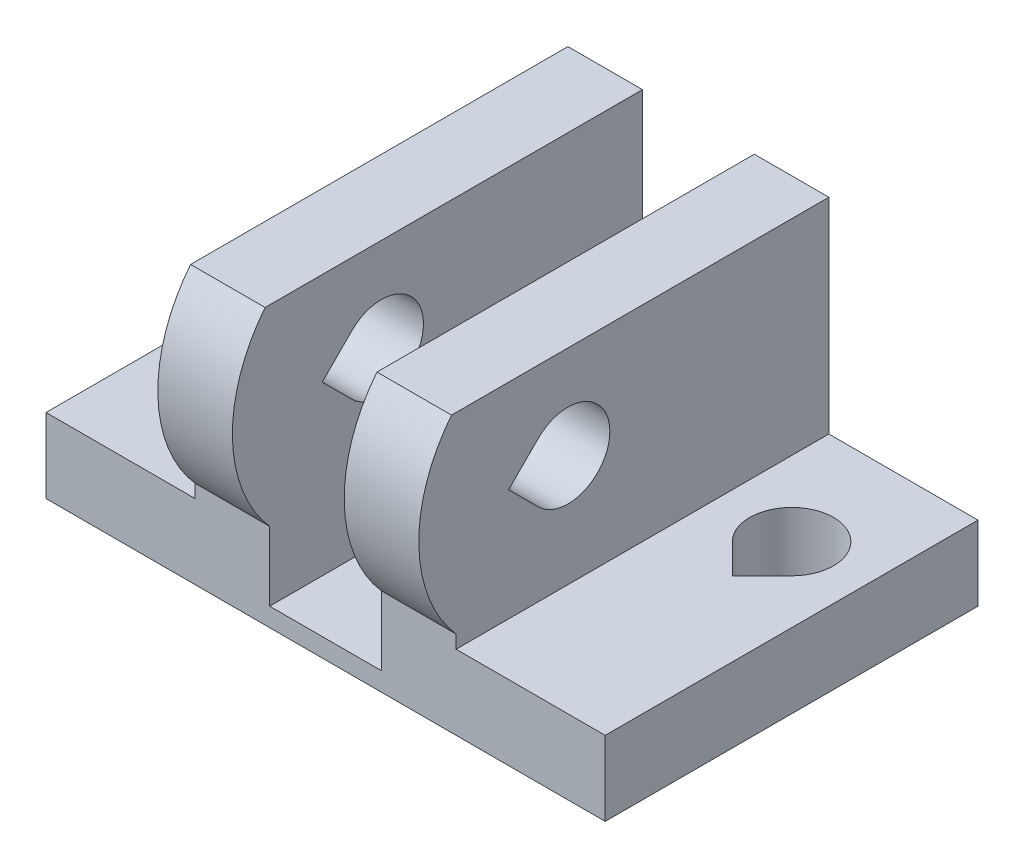
SolidWorks part; units mm, degrees
material "Printed PLA"
ref_plane "Front Plane" through (0, 0, 0) normal (0, 0, 1) x (1, 0, 0)
ref_plane "Top Plane" through (0, 0, 0) normal (0, 1, 0) x (1, 0, 0)
ref_plane "Right Plane" through (0, 0, 0) normal (1, 0, 0) x (0, 0, -1)
sketch "Sketch1" plane through (0, 0, 0) normal (0, 0, 1) x (1, 0, 0)
  line L0 (-15, 0) -> (15, 0)
  line L1 (15, 0) -> (15, 4)
  line L2 (15, 4) -> (7, 4)
  line L3 (7, 4) -> (7, 15)
  line L4 (7, 15) -> (3, 15)
  line L5 (3, 15) -> (3, 4)
  line L6 (3, 4) -> (-3, 4)
  line L7 (-3, 4) -> (-3, 15)
  line L8 (-3, 15) -> (-7, 15)
  line L9 (-7, 15) -> (-7, 4)
  line L10 (-7, 4) -> (-15, 4)
  line L11 (-15, 4) -> (-15, 0)
  dimension "D1" = 30
  dimension "D2" = 4
  dimension "D3" = 6
  dimension "D4" = 4
  dimension "D5" = 15
extrude "Boss-Extrude1" add sketch "Sketch1" along normal blind 20
sketch "Sketch2" plane through (0, 4, 0) normal (0, 1, 0) x (1, 0, 0)
  line L0 (11, -6) -> (-11, -6) construction
  line L1 (0, -6) -> (0, 0) construction
  line L2 (3, 0) -> (-3, 0) construction
  line L3 (-12.591, -7.591) -> (-11, -9.182)
  line L4 (-11, -9.182) -> (-9.409, -7.591)
  line L5 (-11, -9.182) -> (-11, -6) construction
  line L6 (9.409, -7.591) -> (11, -9.182)
  line L7 (11, -9.182) -> (12.591, -7.591)
  line L8 (11, -9.182) -> (11, -6) construction
  arc A0 (-9.409, -7.591) -> (-12.591, -7.591) centre (-11, -6) ccw
  arc A1 (12.591, -7.591) -> (9.409, -7.591) centre (11, -6) ccw
  dimension "D2" = 4.5
  dimension "D1" = 22
  dimension "D3" = 6
extrude "Cut-Extrude1" cut sketch "Sketch2" against normal through all
sketch "Sketch3" plane through (7, 0, 0) normal (1, 0, 0) x (0, 0, -1)
  line L0 (-20, 0) -> (0, 0) construction
  line L1 (-20, 4) -> (-20, 15) construction
  line L2 (-15.591, 11.591) -> (-17.182, 10)
  line L3 (-17.182, 10) -> (-15.591, 8.409)
  line L4 (-17.182, 10) -> (-14, 10) construction
  arc A0 (-15.591, 8.409) -> (-15.591, 11.591) centre (-14, 10) ccw
  dimension "D1" = 4.5
  dimension "D3" = 6
  dimension "D2" = 10
extrude "Cut-Extrude2" cut sketch "Sketch3" against normal through all
sketch "Sketch4" plane through (-3, 0, 0) normal (1, 0, 0) x (0, 0, -1)
  line L0 (-14, 1) -> (-20, 1)
  line L1 (-20, 0) -> (-20, 4) construction
  line L2 (-20, 1) -> (-20, 3.2918)
  arc A0 (-14, 1) -> (-20, 3.2918) centre (-14, 10) ccw
  dimension "D1" = 18
extrude "Cut-Extrude3" cut sketch "Sketch4" along normal up to surface (6 mm away) up to face at (3, 10, 14.841)
sketch "Sketch5" plane through (7, 0, 0) normal (1, 0, 0) x (0, 0, -1)
  line L0 (-20, 4.7085) -> (-20, 15)
  line L1 (-20, 4) -> (-20, 15) construction
  line L4 (-20, 15) -> (-20.245, 15)
  arc A0 (-20.245, 15) -> (-20, 4.7085) centre (-14, 10) ccw
  dimension "D1" = 16
extrude "Boss-Extrude2" add sketch "Sketch5" against normal blind 4
mirror "Mirror1" about plane through (0, 0, 0) normal (1, 0, 0) of "Boss-Extrude2"
